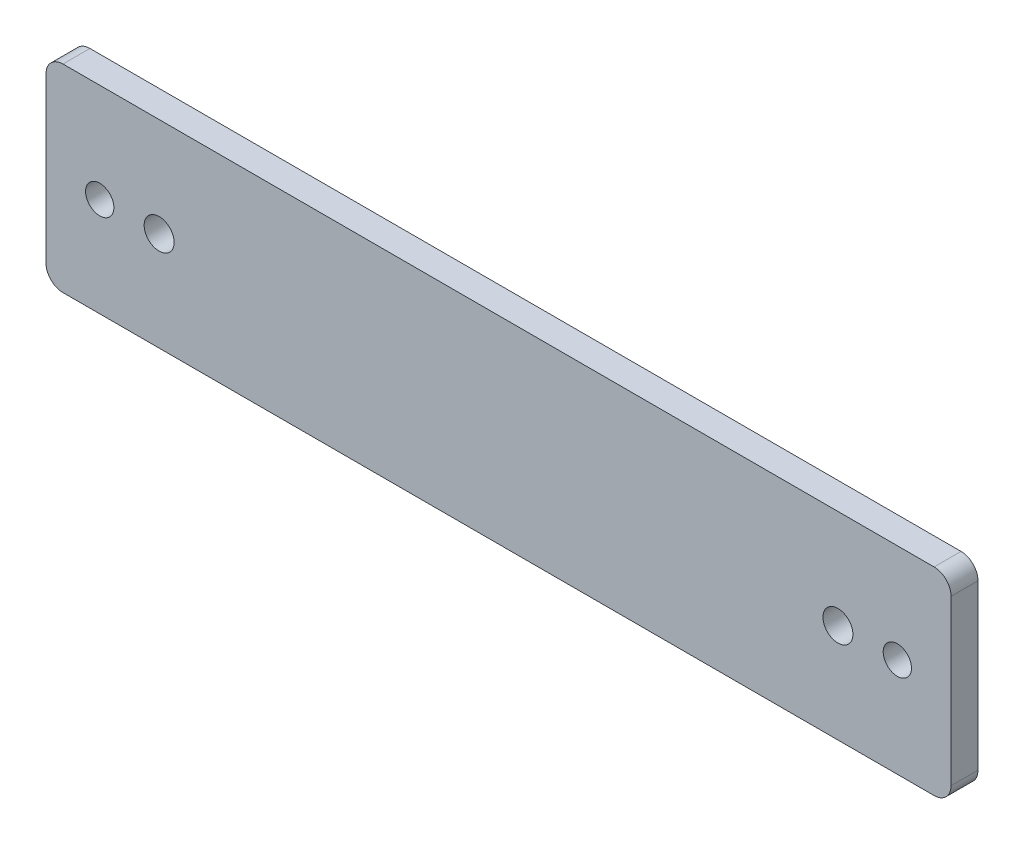
SolidWorks part; units mm, degrees
ref_plane "Front Plane" through (0, 0, 0) normal (0, 0, 1) x (1, 0, 0)
ref_plane "Top Plane" through (0, 0, 0) normal (0, 1, 0) x (1, 0, 0)
ref_plane "Right Plane" through (0, 0, 0) normal (1, 0, 0) x (0, 0, -1)
sketch "Sketch1" plane through (0, 0, 0) normal (0, 0, 1) x (1, 0, 0)
  line L0 (-70.5, 0) -> (70.5, 0) construction
  line L1 (-80, -17.5) -> (80, -17.5)
  line L2 (-80, -17.5) -> (-80, 17.5)
  line L3 (-80, 17.5) -> (80, 17.5)
  line L4 (80, -17.5) -> (80, 17.5)
  line L5 (-80, -17.5) -> (80, 17.5) construction
  line L6 (-80, 17.5) -> (80, -17.5) construction
  line L7 (-60, 0) -> (60, 0) construction
  line L8 (-77, -17.5) -> (77, -17.5) construction
  line L9 (-77, -17.5) -> (-77, 17.5) construction
  line L10 (-77, 17.5) -> (77, 17.5) construction
  line L11 (77, -17.5) -> (77, 17.5) construction
  line L12 (-77, -17.5) -> (77, 17.5) construction
  line L13 (-77, 17.5) -> (77, -17.5) construction
  circle A0 centre (-70.5, 0) radius 2.5
  circle A1 centre (70.5, 0) radius 2.5
  point P10 (0, 0)
  point P24 (0, 0)
  dimension "D6" = 5
  dimension "D1" = 35
  dimension "D2" = 160
  dimension "D3" = 141
  dimension "D4" = 154
  dimension "D5" = 35
  dimension "D10" = 120
extrude "Boss-Extrude1" add sketch "Sketch1" along normal blind 4.7625
hole_wizard "M5 Clearance Hole1" positions "Sketch2" profile "Sketch3" hole size "M5" standard "ANSI Metric" end condition through all
sketch "Sketch2" plane through (0, 0, 4.7625) normal (0, 0, 1) x (1, 0, 0)
  point P0 (-60, 0)
  point P3 (60, 0)
sketch "Sketch3" plane through (-60, 0, 4.7625) normal (1, 0, 0) x (0, -1, 0)
  line L0 (0, 0) -> (0, 4.7625)
  line L1 (0, 4.7625) -> (2.65, 4.7625)
  line L2 (2.65, 4.7625) -> (2.65, 0)
  line L5 (2.65, 0) -> (0, 0)
  line L11 (0, -6.35) -> (0, 107.95) construction
  dimension "Thru Hole Dia." = 5.3
  dimension "Thru Hole Depth" = 4.7625
fillet "Fillet1" radius 3 4 edges at (80, -17.5, 2.3813) (-80, 17.5, 2.3813) (80, 17.5, 2.3813) (-80, -17.5, 2.3813)
